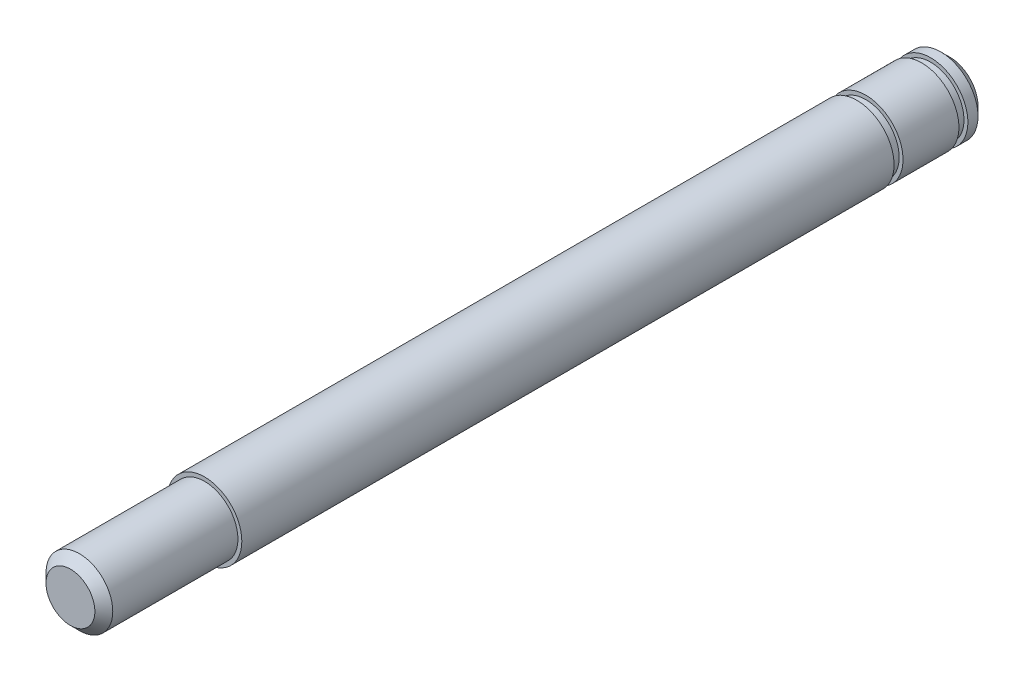
SolidWorks part; units mm, degrees
ref_plane "Front Plane" through (0, 0, 0) normal (0, 0, 1) x (1, 0, 0)
ref_plane "Top Plane" through (0, 0, 0) normal (0, 1, 0) x (1, 0, 0)
ref_plane "Right Plane" through (0, 0, 0) normal (1, 0, 0) x (0, 0, -1)
sketch "Sketch1" plane through (0, 0, 0) normal (0, 0, 1) x (1, 0, 0)
  circle A0 centre (0, 0) radius 1.5875
  dimension "D1" = 3.175
extrude "Boss-Extrude1" add sketch "Sketch1" along normal mid plane 31.75
sketch "Sketch2" plane through (0, 0, 15.875) normal (0, 0, 1) x (1, 0, 0)
  circle A0 centre (0, 0) radius 1.4224
  dimension "D1" = 2.8448
extrude "Boss-Extrude2" add sketch "Sketch2" along normal blind 5.715
cosmetic thread "Cosmetic Thread1" parameters "D2"=2.0879
ref_plane "Plane1" through (0, 0, -15.0622) normal (0, 0, -1) x (-1, 0, 0)
sketch "Sketch3" plane through (0, 0, -15.0622) normal (0, 0, -1) x (-1, 0, 0)
  circle A0 centre (0, 0) radius 1.5875 construction
  circle A1 centre (0, 0) radius 1.4224 construction
  circle A2 centre (0, 0) radius 1.5875
  circle A3 centre (0, 0) radius 1.4224
extrude "Cut-Extrude1" cut sketch "Sketch3" against normal blind 0.381 contours A2 | A3
ref_plane "Plane2" through (0, 0, -12.3) normal (0, 0, -1) x (-1, 0, 0)
sketch "Sketch4" plane through (0, 0, -12.3) normal (0, 0, -1) x (-1, 0, 0)
  circle A0 centre (0, 0) radius 1.4224 construction
  circle A1 centre (0, 0) radius 1.5875
  circle A2 centre (0, 0) radius 1.5875
  circle A3 centre (0, 0) radius 1.4224
  dimension "D1" = 0
extrude "Cut-Extrude2" cut sketch "Sketch4" against normal blind 0.381 contours A3 | A2
chamfer "Chamfer1" distance 0.381 2 edges at (1.4224, 0, 21.59) (1.5875, 0, -15.875)
